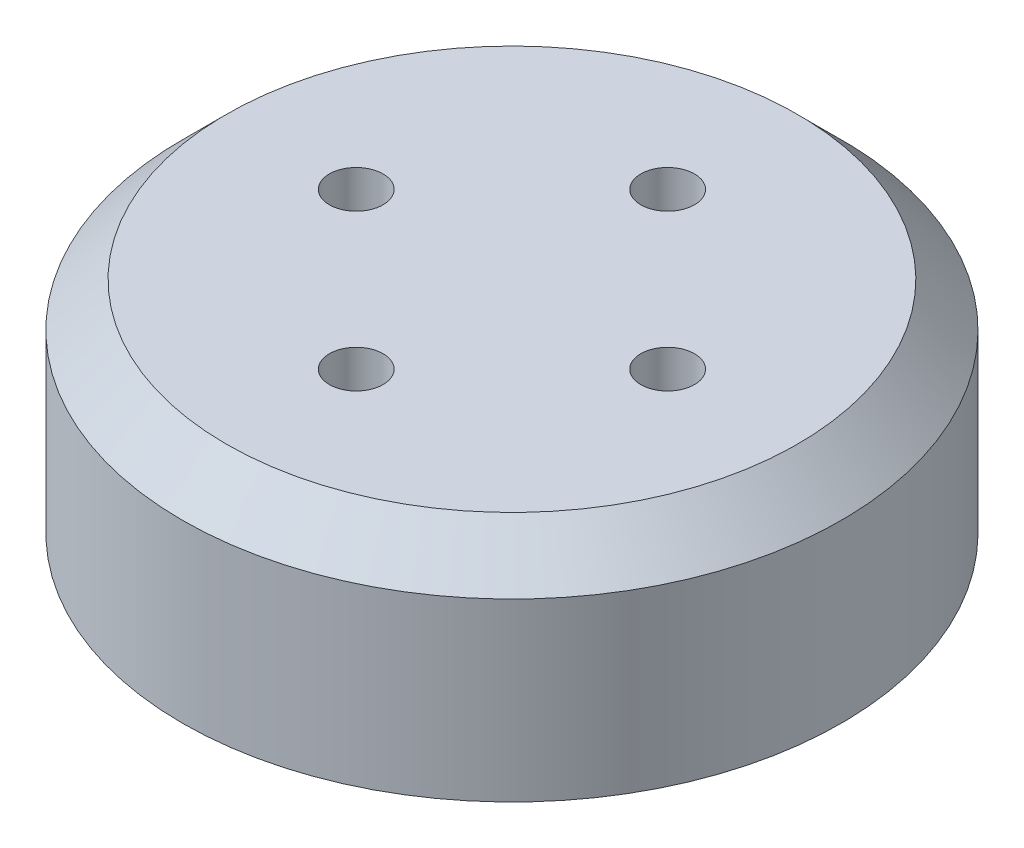
SolidWorks part; units mm, degrees
ref_plane "Front Plane" through (0, 0, 0) normal (0, 0, 1) x (1, 0, 0)
ref_plane "Top Plane" through (0, 0, 0) normal (0, 1, 0) x (1, 0, 0)
ref_plane "Right Plane" through (0, 0, 0) normal (1, 0, 0) x (0, 0, -1)
sketch "Sketch1" plane through (0, 0, 0) normal (1, 0, 0) x (0, 0, -1)
  line L0 (0, 0) -> (0, -6.35)
  line L1 (0, -6.35) -> (-4.975, -6.35)
  line L2 (-4.975, -6.35) -> (-4.975, 0)
  line L3 (-4.975, 0) -> (-19.05, 0)
  line L4 (-19.05, 0) -> (-19.05, 12.7)
  line L5 (-19.05, 12.7) -> (0, 12.7)
  line L6 (0, 12.7) -> (0, 0)
  dimension "D1" = 4.975
  dimension "D2" = 19.05
  dimension "D3" = 6.35
  dimension "D4" = 12.7
revolve "Revolve1" add sketch "Sketch1" angle 360 about L6
sketch "Sketch2" plane through (0, 12.7, 0) normal (0, 1, 0) x (1, 0, 0)
  line L0 (-9, 0) -> (9, 0) construction
  line L1 (0, 9) -> (0, -9) construction
  circle A0 centre (0, 9) radius 1.55
  circle A1 centre (0, -9) radius 1.55
  circle A2 centre (9, 0) radius 1.55
  circle A3 centre (-9, 0) radius 1.55
  point P8 (0, 0)
  point P9 (-2.2556, 9.5352)
  point P10 (0, 0)
  point P12 (-9.3644, 1.2987)
  dimension "D1" = 3.1
  dimension "D2" = 18
extrude "Cut-Extrude1" cut sketch "Sketch2" against normal through all
sketch "Sketch3" plane through (0, 0, 0) normal (0, -1, 0) x (1, 0, 0)
  line L1 (5.08, 5.08) -> (-5.08, 5.08) construction
  line L2 (5.08, 5.08) -> (5.08, -5.08) construction
  line L3 (5.08, -5.08) -> (-5.08, -5.08) construction
  line L4 (-5.08, 5.08) -> (-5.08, -5.08) construction
  line L5 (0, -5.08) -> (0, 5.08) construction
  line L6 (5.08, 0) -> (-5.08, 0) construction
  circle A0 centre (-5.08, -5.08) radius 1.45
  circle A1 centre (-5.08, 5.08) radius 1.45
  circle A2 centre (5.08, 5.08) radius 1.45
  circle A3 centre (5.08, -5.08) radius 1.45
  point P2 (0, 0)
  dimension "D1" = 2.9
  dimension "D2" = 10.16
extrude "Boss-Extrude1" add sketch "Sketch3" along normal blind 1.27
chamfer "Chamfer1" distance 2.54 angle 45 1 edges at (0, 12.7, 19.05)
